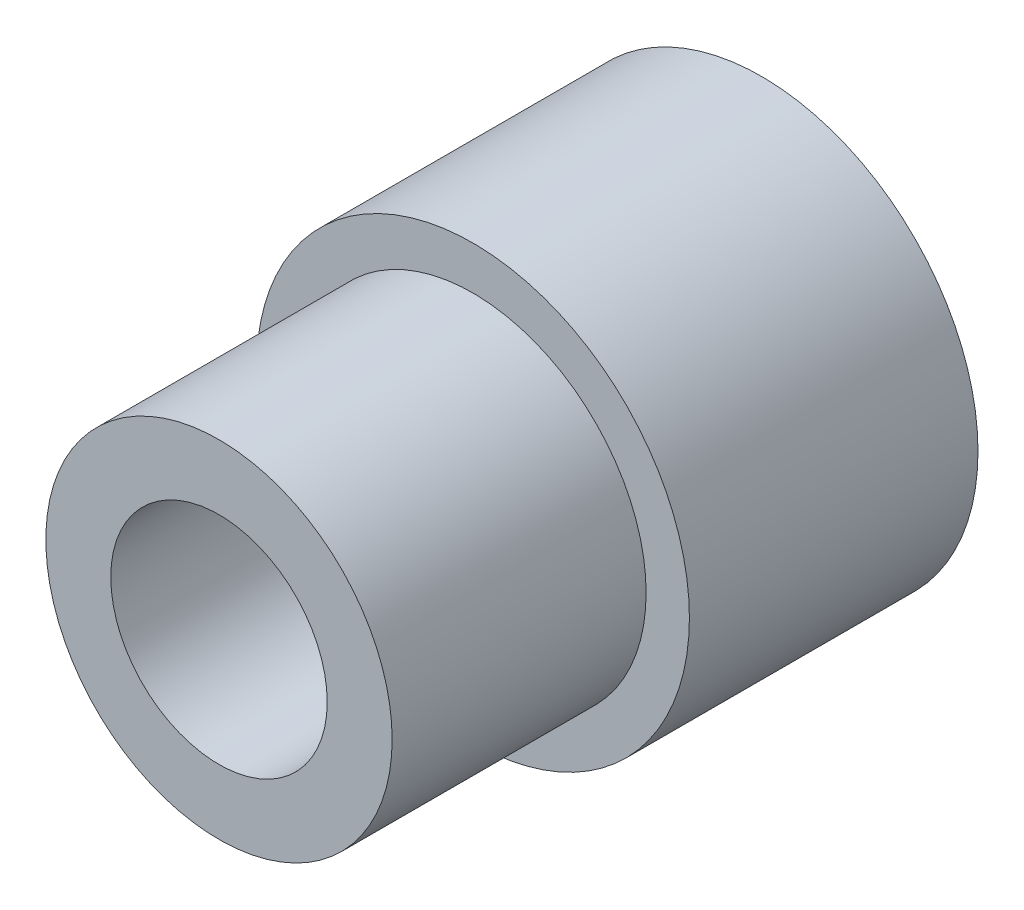
SolidWorks part; units mm, degrees
ref_plane "Front Plane" through (0, 0, 0) normal (0, 0, 1) x (1, 0, 0)
ref_plane "Top Plane" through (0, 0, 0) normal (0, 1, 0) x (1, 0, 0)
ref_plane "Right Plane" through (0, 0, 0) normal (1, 0, 0) x (0, 0, -1)
sketch "Sketch1" plane through (0, 0, 0) normal (0, 0, 1) x (1, 0, 0)
  circle A0 centre (0, 0) radius 9.525
  dimension "D1" = 19.05
extrude "Boss-Extrude1" add sketch "Sketch1" along normal blind 12.7
sketch "Sketch2" plane through (0, 0, 12.7) normal (0, 0, 1) x (1, 0, 0)
  circle A0 centre (0, 0) radius 7.62
  dimension "D1" = 15.24
extrude "Boss-Extrude2" add sketch "Sketch2" along normal blind 11.176
sketch "Sketch3" plane through (0, 0, 23.876) normal (0, 0, 1) x (1, 0, 0)
  circle A0 centre (0, 0) radius 4.7625
  dimension "D1" = 9.525
extrude "Cut-Extrude1" cut sketch "Sketch3" against normal through all
